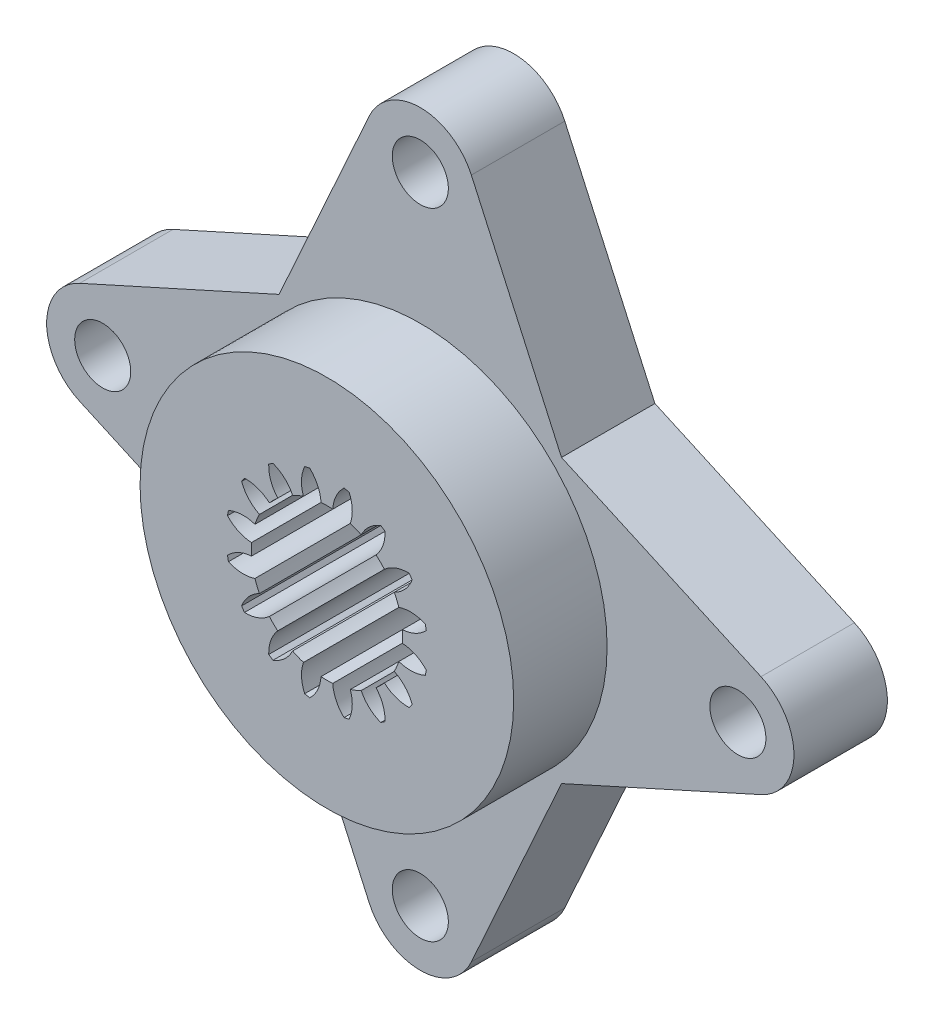
SolidWorks part; units mm, degrees
ref_plane "Alzado" through (0, 0, 0) normal (0, 0, 1) x (1, 0, 0)
ref_plane "Planta" through (0, 0, 0) normal (0, 1, 0) x (1, 0, 0)
ref_plane "Vista lateral" through (0, 0, 0) normal (1, 0, 0) x (0, 0, -1)
sketch "Croquis1" plane through (0, 0, 0) normal (0, 0, 1) x (1, 0, 0)
  circle A0 centre (0, 0) radius 10
  circle A1 centre (0, 0) radius 2
  dimension "D1" = 4
  dimension "D2" = 20
extrude "Saliente-Extruir1" add sketch "Croquis1" along normal blind 10
sketch "Croquis2" plane through (0, 0, 10) normal (0, 0, 1) x (1, 0, 0)
  line L0 (0.9184, 5.3213) -> (1.1879, 5.2677)
  line L1 (2.8848, 4.5648) -> (3.1134, 4.4121)
  line L2 (4.4121, 3.1134) -> (4.5648, 2.8848)
  line L3 (5.2677, 1.1879) -> (5.3213, 0.9184)
  line L4 (-1.0531, 5.2945) -> (1.0531, -5.2945) construction
  line L5 (5.3213, -0.9184) -> (5.2677, -1.1879)
  line L6 (4.5648, -2.8848) -> (4.4121, -3.1134)
  line L7 (3.1134, -4.4121) -> (2.8848, -4.5648)
  line L8 (1.1879, -5.2677) -> (0.9184, -5.3213)
  line L9 (-0.9184, -5.3213) -> (-1.1879, -5.2677)
  line L10 (-2.8848, -4.5648) -> (-3.1134, -4.4121)
  line L11 (-4.4121, -3.1134) -> (-4.5648, -2.8848)
  line L12 (-5.2677, -1.1879) -> (-5.3213, -0.9184)
  line L13 (-5.3213, 0.9184) -> (-5.2677, 1.1879)
  line L14 (-4.5648, 2.8848) -> (-4.4121, 3.1134)
  line L15 (-1.1879, 5.2677) -> (-0.9184, 5.3213)
  line L16 (-3.1134, 4.4121) -> (-2.8848, 4.5648)
  arc A0 (1.2542, 3.8499) -> (1.1879, 5.2677) centre (-0.561, 4.4755) ccw
  arc A1 (0.9184, 5.3213) -> (0.3145, 4.0368) centre (2.231, 3.9201) ccw
  arc A2 (0.3145, 4.0368) -> (-0.3145, 4.0368) centre (0, 0) ccw
  arc A3 (2.632, 3.0768) -> (3.1134, 4.4121) centre (1.1944, 4.3495) ccw
  arc A4 (2.8848, 4.5648) -> (1.8354, 3.6091) centre (3.5613, 2.768) ccw
  arc A5 (1.8354, 3.6091) -> (1.2542, 3.8499) centre (0, 0) ccw
  arc A6 (3.6091, 1.8354) -> (4.5648, 2.8848) centre (2.768, 3.5613) ccw
  arc A7 (4.4121, 3.1134) -> (3.0768, 2.632) centre (4.3495, 1.1944) ccw
  arc A8 (3.0768, 2.632) -> (2.632, 3.0768) centre (0, 0) ccw
  arc A9 (4.0368, 0.3145) -> (5.3213, 0.9184) centre (3.9201, 2.231) ccw
  arc A10 (5.2677, 1.1879) -> (3.8499, 1.2542) centre (4.4755, -0.561) ccw
  arc A11 (3.8499, 1.2542) -> (3.6091, 1.8354) centre (0, 0) ccw
  arc A12 (3.8499, -1.2542) -> (5.2677, -1.1879) centre (4.4755, 0.561) ccw
  arc A13 (5.3213, -0.9184) -> (4.0368, -0.3145) centre (3.9201, -2.231) ccw
  arc A14 (4.0368, -0.3145) -> (4.0368, 0.3145) centre (0, 0) ccw
  arc A15 (3.0768, -2.632) -> (4.4121, -3.1134) centre (4.3495, -1.1944) ccw
  arc A16 (4.5648, -2.8848) -> (3.6091, -1.8354) centre (2.768, -3.5613) ccw
  arc A17 (3.6091, -1.8354) -> (3.8499, -1.2542) centre (0, 0) ccw
  arc A18 (1.8354, -3.6091) -> (2.8848, -4.5648) centre (3.5613, -2.768) ccw
  arc A19 (3.1134, -4.4121) -> (2.632, -3.0768) centre (1.1944, -4.3495) ccw
  arc A20 (2.632, -3.0768) -> (3.0768, -2.632) centre (0, 0) ccw
  arc A21 (0.3145, -4.0368) -> (0.9184, -5.3213) centre (2.231, -3.9201) ccw
  arc A22 (1.1879, -5.2677) -> (1.2542, -3.8499) centre (-0.561, -4.4755) ccw
  arc A23 (1.2542, -3.8499) -> (1.8354, -3.6091) centre (0, 0) ccw
  arc A24 (-1.2542, -3.8499) -> (-1.1879, -5.2677) centre (0.561, -4.4755) ccw
  arc A25 (-0.9184, -5.3213) -> (-0.3145, -4.0368) centre (-2.231, -3.9201) ccw
  arc A26 (-0.3145, -4.0368) -> (0.3145, -4.0368) centre (0, 0) ccw
  arc A27 (-2.632, -3.0768) -> (-3.1134, -4.4121) centre (-1.1944, -4.3495) ccw
  arc A28 (-2.8848, -4.5648) -> (-1.8354, -3.6091) centre (-3.5613, -2.768) ccw
  arc A29 (-1.8354, -3.6091) -> (-1.2542, -3.8499) centre (0, 0) ccw
  arc A30 (-3.6091, -1.8354) -> (-4.5648, -2.8848) centre (-2.768, -3.5613) ccw
  arc A31 (-4.4121, -3.1134) -> (-3.0768, -2.632) centre (-4.3495, -1.1944) ccw
  arc A32 (-3.0768, -2.632) -> (-2.632, -3.0768) centre (0, 0) ccw
  arc A33 (-4.0368, -0.3145) -> (-5.3213, -0.9184) centre (-3.9201, -2.231) ccw
  arc A34 (-5.2677, -1.1879) -> (-3.8499, -1.2542) centre (-4.4755, 0.561) ccw
  arc A35 (-3.8499, -1.2542) -> (-3.6091, -1.8354) centre (0, 0) ccw
  arc A36 (-3.8499, 1.2542) -> (-5.2677, 1.1879) centre (-4.4755, -0.561) ccw
  arc A37 (-5.3213, 0.9184) -> (-4.0368, 0.3145) centre (-3.9201, 2.231) ccw
  arc A38 (-4.0368, 0.3145) -> (-4.0368, -0.3145) centre (0, 0) ccw
  arc A39 (-3.0768, 2.632) -> (-4.4121, 3.1134) centre (-4.3495, 1.1944) ccw
  arc A40 (-4.5648, 2.8848) -> (-3.6091, 1.8354) centre (-2.768, 3.5613) ccw
  arc A41 (-3.6091, 1.8354) -> (-3.8499, 1.2542) centre (0, 0) ccw
  arc A42 (-1.8354, 3.6091) -> (-2.8848, 4.5648) centre (-3.5613, 2.768) ccw
  arc A43 (-3.1134, 4.4121) -> (-2.632, 3.0768) centre (-1.1944, 4.3495) ccw
  arc A44 (-2.632, 3.0768) -> (-3.0768, 2.632) centre (0, 0) ccw
  arc A62 (-0.3145, 4.0368) -> (-0.9184, 5.3213) centre (-2.231, 3.9201) ccw
  arc A63 (-1.1879, 5.2677) -> (-1.2542, 3.8499) centre (0.561, 4.4755) ccw
  arc A88 (-1.2542, 3.8499) -> (-1.8354, 3.6091) centre (0, 0) ccw
  point P119 (0, 0)
  dimension "D1" = 1.92
  dimension "D2" = 4.049
  dimension "D3" = 16
extrude "Cortar-Extruir1" cut sketch "Croquis2" against normal blind 20 and the other way blind 10
sketch "Croquis3" plane through (0, 0, 0) normal (0, 0, -1) x (-1, 0, 0)
  line L0 (-2.7339, 18.2353) -> (-7.5583, 7.5583)
  line L1 (2.7339, 18.2353) -> (7.5583, 7.5583)
  line L2 (18.2353, 2.7339) -> (7.5583, 7.5583)
  line L3 (18.2353, -2.7339) -> (7.5583, -7.5583)
  line L4 (2.7339, -18.2353) -> (7.5583, -7.5583)
  line L5 (-2.7339, -18.2353) -> (-7.5583, -7.5583)
  line L6 (-18.2353, -2.7339) -> (-7.5583, -7.5583)
  line L7 (-18.2353, 2.7339) -> (-7.5583, 7.5583)
  circle A0 centre (0, 17) radius 1.5
  arc A1 (2.7339, 18.2353) -> (-2.7339, 18.2353) centre (0, 17) ccw
  arc A2 (18.2353, -2.7339) -> (18.2353, 2.7339) centre (17, 0) ccw
  circle A3 centre (17, 0) radius 1.5
  circle A4 centre (0, 0) radius 10 construction
  circle A5 centre (0, 0) radius 10
  arc A6 (-2.7339, -18.2353) -> (2.7339, -18.2353) centre (0, -17) ccw
  circle A7 centre (0, -17) radius 1.5
  arc A8 (-18.2353, 2.7339) -> (-18.2353, -2.7339) centre (-17, 0) ccw
  circle A9 centre (-17, 0) radius 1.5
  point P24 (0, 0)
  point P26 (0, 0)
  point P32 (0, 0)
  dimension "D1" = 3
  dimension "D2" = 6
  dimension "D3" = 17
extrude "Saliente-Extruir2" add sketch "Croquis3" against normal blind 5
